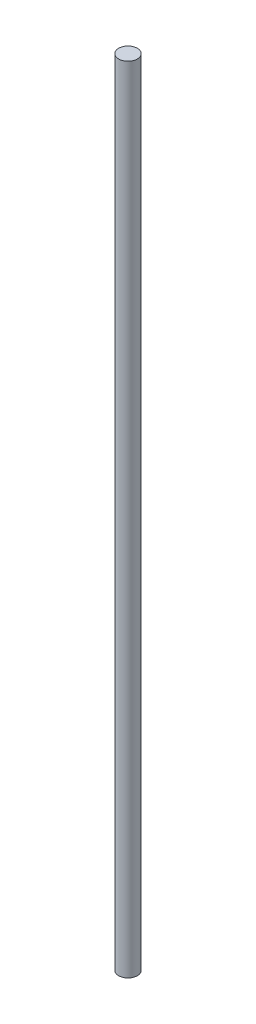
SolidWorks part; units mm, degrees
ref_plane "Front Plane" through (0, 0, 0) normal (0, 0, 1) x (1, 0, 0)
ref_plane "Top Plane" through (0, 0, 0) normal (0, 1, 0) x (1, 0, 0)
ref_plane "Right Plane" through (0, 0, 0) normal (1, 0, 0) x (0, 0, -1)
sketch "Sketch1" plane through (0, 0, 0) normal (0, 1, 0) x (1, 0, 0)
  circle A0 centre (0, 0) radius 0.5969
  dimension "D1" = 1.1938
extrude "Boss-Extrude1" add sketch "Sketch1" along normal blind 50.8
